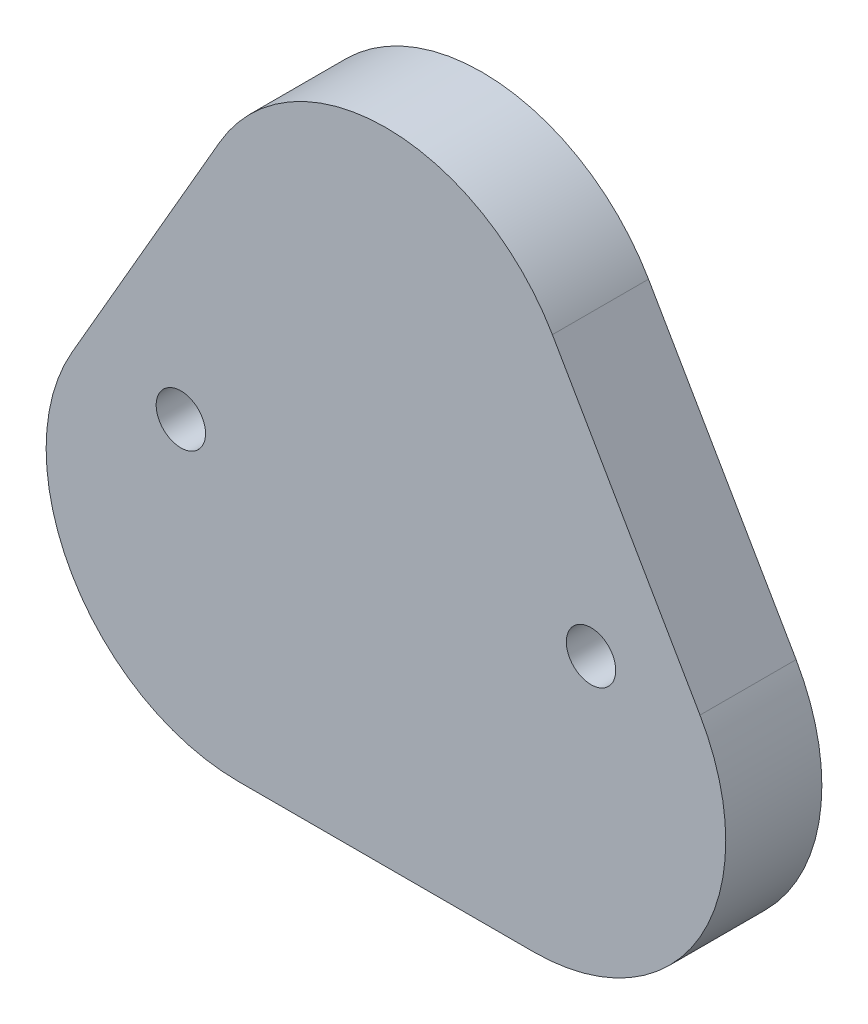
SolidWorks part; units mm, degrees
material "Acrylic (Medium-high impact)"
ref_plane "Front Plane" through (0, 0, 0) normal (0, 0, 1) x (1, 0, 0)
ref_plane "Top Plane" through (0, 0, 0) normal (0, 1, 0) x (1, 0, 0)
ref_plane "Right Plane" through (0, 0, 0) normal (1, 0, 0) x (0, 0, -1)
sketch "Sketch1" plane through (0, 0, 0) normal (0, 0, 1) x (1, 0, 0)
  line L0 (0.8385, 39.5653) -> (-30.9115, -15.4273)
  line L1 (-30.9115, -15.4273) -> (32.5885, -15.4273)
  line L2 (32.5885, -15.4273) -> (0.8385, 39.5653)
  dimension "D1" = 63.5
extrude "Boss-Extrude1" add sketch "Sketch1" along normal blind 6.35 contours L0 L1 L2
ref_plane "Plane1" through (17.3419, 30.037, 0) normal (0.5, 0.866, 0) x (0, 0, 1)
sketch "Sketch3" plane through (17.3419, 30.037, 0) normal (0.5, 0.866, 0) x (0, 0, 1)
  line L0 (6.35, -19.0565) -> (6.35, -2.277) construction
ref_plane "Plane2" through (-16.9227, 29.3109, 0) normal (0.5, -0.866, 0) x (0, 0, -1)
sketch "Sketch4" plane through (-16.9227, 29.3109, 0) normal (0.5, -0.866, 0) x (0, 0, -1)
  line L0 (-6.35, 20.5088) -> (-6.35, 86.9434) construction
hole_wizard "#4 Clearance Hole1" positions "3DSketch1" profile "Sketch2" hole size "#4" standard "ANSI Inch"
sketch3d "3DSketch1"
  line L0 (0.8385, 39.5653, 6.35) -> (-30.9115, -15.4273, 6.35) construction
  line L1 (32.5885, -15.4273, 6.35) -> (0.8385, 39.5653, 6.35) construction
  line L2 (0.8385, 39.5653, 6.35) -> (58.3725, 72.7826, 6.35) construction
  line L3 (0.8385, 39.5653, 6.35) -> (15.3699, 31.1756, 6.35) construction
  point P0 (-12.7123, 3.3947, 6.35)
  point P4 (14.3892, 3.3947, 6.35)
  dimension "D1" = 6.35
  dimension "D3" = 6.35
  dimension "D5" = 38.1
  dimension "D6" = 38.1
sketch "Sketch2" plane through (-12.7123, 3.3947, 6.35) normal (1, 0, 0) x (0, -1, 0)
  line L0 (0, 0) -> (0, 10.6326)
  line L1 (0, 10.6326) -> (1.6319, 9.652)
  line L2 (1.6319, 9.652) -> (1.6319, 0)
  line L5 (1.6319, 0) -> (0, 0)
  line L10 (0, 10.6326) -> (-1.6319, 9.652) construction
  line L11 (0, -6.35) -> (0, 107.95) construction
  dimension "Hole Dia." = 3.2639
  dimension "Hole Depth" = 9.652
  dimension "Drill Angle" = 118
fillet "Fillet1" radius 12.7 3 edges at (32.5885, -15.4273, 3.175) (-30.9115, -15.4273, 3.175) (0.8385, 39.5653, 3.175)
